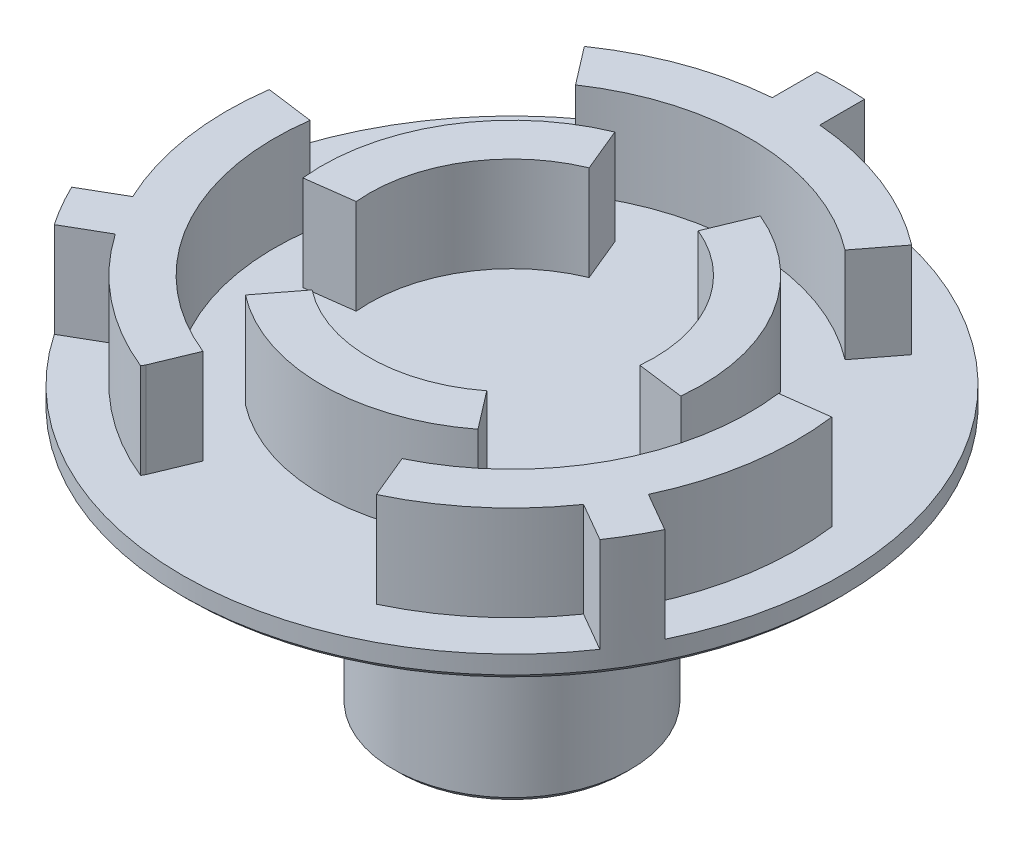
SolidWorks part; units mm, degrees
other "Markup1"
sketch "Sketch9" plane through (44.0525, -34.13, 44.0525) normal (0.2093, -0.9777, 0.0152) x (0.5498, 0.1048, -0.8287)
sketch "Sketch10" plane through (44.0525, -34.13, 44.0525) normal (0.2093, -0.9777, 0.0152) x (0.5498, 0.1048, -0.8287)
sketch "Sketch11" plane through (44.0525, -34.13, 44.0525) normal (0.2093, -0.9777, 0.0152) x (0.5498, 0.1048, -0.8287)
material "PLA"
ref_plane "Front Plane" through (0, 0, 0) normal (0, 0, 1) x (1, 0, 0)
ref_plane "Top Plane" through (0, 0, 0) normal (0, 1, 0) x (1, 0, 0)
ref_plane "Right Plane" through (0, 0, 0) normal (1, 0, 0) x (0, 0, -1)
sketch "Sketch1" plane through (0, 0, 0) normal (0, 1, 0) x (1, 0, 0)
  circle A0 centre (0, 0) radius 44.0525
  dimension "D1" = 88.105
extrude "Boss-Extrude1" add sketch "Sketch1" along normal blind 3.175
sketch "Sketch2" plane through (0, 0, 0) normal (0, -1, 0) x (1, 0, 0)
  circle A0 centre (0, 0) radius 15.875
  dimension "D1" = 31.75
extrude "Boss-Extrude2" add sketch "Sketch2" along normal blind 34.13
sketch "Sketch3" plane through (0, 3.175, 0) normal (0, 1, 0) x (1, 0, 0)
  circle A0 centre (0, 0) radius 19.05
  circle A1 centre (0, 0) radius 25.4
  dimension "D1" = 38.1
  dimension "D2" = 50.8
extrude "Boss-Extrude3" add sketch "Sketch3" along normal blind 12.7
sketch "Sketch4" plane through (0, 3.175, 0) normal (0, 1, 0) x (1, 0, 0)
  line L0 (0, 0) -> (0, 33.2198) construction
  line L1 (0, 0) -> (11.4621, 27.672)
  line L2 (0, 0) -> (-12.0669, 29.132)
  line L3 (-12.0669, 29.132) -> (11.4621, 27.672)
  dimension "D1" = 22.5
  dimension "D2" = 22.5
extrude "Cut-Extrude2" cut sketch "Sketch4" along normal through all
pattern_circular "CirPattern1" count 3 over 360 about axis through (0, 0, -0.4543) along (0, 1, 0) of "Cut-Extrude2"
sketch "Sketch5" plane through (0, 3.175, 0) normal (0, 1, 0) x (1, 0, 0)
  circle A0 centre (0, 0) radius 31.75
  circle A1 centre (0, 0) radius 38.1
  dimension "D1" = 63.5
  dimension "D2" = 76.2
extrude "Boss-Extrude5" add sketch "Sketch5" along normal blind 12.7
sketch "Sketch6" plane through (0, 15.875, 0) normal (0, 1, 0) x (1, 0, 0)
  line L0 (24.5189, 31.9536) -> (30.848, 40.2018)
  line L1 (30.848, 40.2018) -> (52.89, 5.2125)
  line L2 (18.1732, 23.6838) -> (24.5189, 31.9536)
  line L3 (30.848, 4.0612) -> (39.5926, 5.2125)
  line L7 (52.89, 5.2125) -> (39.5926, 5.2125)
  line L8 (18.1732, 23.6838) -> (30.848, 4.0612)
extrude "Cut-Extrude4" cut sketch "Sketch6" against normal blind 12.7
pattern_circular "CirPattern3" count 3 over 360 about axis through (1.189, 0, -0.687) along (0, 1, 0) of "Cut-Extrude4"
sketch "Sketch7" plane through (0, 3.175, 0) normal (0, 1, 0) x (1, 0, 0)
  line L1 (3.175, 35.8606) -> (3.175, 43.9379)
  line L2 (-3.175, 35.8606) -> (-3.175, 43.9379)
  arc A1 (3.175, 35.8606) -> (-3.175, 35.8606) centre (0, 0) ccw
  arc A2 (3.175, 43.9379) -> (-3.175, 43.9379) centre (0, 0) ccw
extrude "Boss-Extrude6" add sketch "Sketch7" along normal blind 12.7
pattern_circular "CirPattern4" count 3 over 360 about axis through (0, 0, 0) along (0, 1, 0) of "Boss-Extrude6"
sketch "Sketch8" plane through (0, -34.13, 0) normal (0, -1, 0) x (1, 0, 0)
  circle A2 centre (0, 0) radius 12.7
  circle A3 centre (0, 0) radius 12.7
  dimension "D1" = 3.175
extrude "Cut-Extrude5" cut sketch "Sketch8" against normal up to surface (34.13 mm away) up to face at (0, 0, -15.875)
chamfer "Chamfer1" distance 0.762 angle 45 2 edges at (0, 0, 44.0525) (0, -34.13, -15.875)
